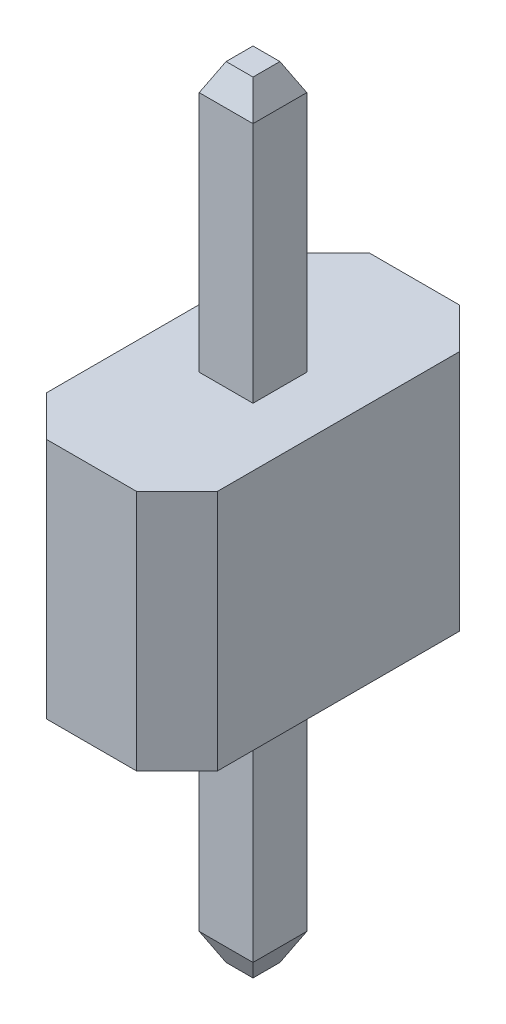
SolidWorks part; units mm, degrees
ref_plane "前视基准面" through (0, 0, 0) normal (0, 0, 1) x (1, 0, 0)
ref_plane "上视基准面" through (0, 0, 0) normal (0, 1, 0) x (1, 0, 0)
ref_plane "右视基准面" through (0, 0, 0) normal (1, 0, 0) x (0, 0, -1)
sketch "草图1" plane through (0, 0, 0) normal (0, 1, 0) x (1, 0, 0)
  line L1 (-0.635, 1.2) -> (0.635, 1.2)
  line L2 (-0.635, 1.2) -> (-0.635, -1.2)
  line L3 (-0.635, -1.2) -> (0.635, -1.2)
  line L4 (0.635, 1.2) -> (0.635, -1.2)
  line L5 (-0.635, 1.2) -> (0.635, -1.2) construction
  line L6 (-0.635, -1.2) -> (0.635, 1.2) construction
  point P0 (0, 0)
  dimension "D1" = 1.27
  dimension "D2" = 2.4
extrude "凸台-拉伸1" add sketch "草图1" along normal blind 1.8
sketch "草图2" plane through (0, 1.8, 0) normal (0, 1, 0) x (1, 0, 0)
  line L1 (-0.2, 0.2) -> (0.2, 0.2)
  line L2 (-0.2, 0.2) -> (-0.2, -0.2)
  line L3 (-0.2, -0.2) -> (0.2, -0.2)
  line L4 (0.2, 0.2) -> (0.2, -0.2)
  line L5 (-0.2, 0.2) -> (0.2, -0.2) construction
  line L6 (-0.2, -0.2) -> (0.2, 0.2) construction
  point P0 (0, 0)
  dimension "D1" = 0.4
extrude "凸台-拉伸2" add sketch "草图2" along normal blind 2 and the other way blind 3.8
sketch "草图3" plane through (0, 1.8, 0) normal (0, 1, 0) x (1, 0, 0)
  line L0 (-0.335, 1.2) -> (-0.635, 0.9)
  line L1 (0.635, 1.2) -> (-0.635, 1.2) construction
  line L2 (-0.635, 1.2) -> (-0.635, -1.2) construction
  line L3 (-0.635, 0.9) -> (-0.635, 1.2)
  line L4 (-0.635, 1.2) -> (-0.335, 1.2)
  line L5 (0, 1.2) -> (0, -1.2) construction
  line L6 (-0.635, -1.2) -> (0.635, -1.2) construction
  line L7 (-0.635, 0) -> (0.635, 0) construction
  line L8 (0.635, -1.2) -> (0.635, 1.2) construction
  line L9 (0.635, 1.2) -> (0.335, 1.2)
  line L10 (0.635, 0.9) -> (0.635, 1.2)
  line L11 (0.335, 1.2) -> (0.635, 0.9)
  line L12 (0.335, -1.2) -> (0.635, -0.9)
  line L13 (0.635, -0.9) -> (0.635, -1.2)
  line L14 (0.635, -1.2) -> (0.335, -1.2)
  line L15 (-0.635, -1.2) -> (-0.335, -1.2)
  line L16 (-0.635, -0.9) -> (-0.635, -1.2)
  line L17 (-0.335, -1.2) -> (-0.635, -0.9)
  dimension "D1" = 0.3
extrude "切除-拉伸1" cut sketch "草图3" against normal through all
chamfer "倒角1" distance 0.2 distance2 0.1 4 edges at (0, 3.8, 0.2) (-0.2, 3.8, 0) (0, 3.8, -0.2) (0.2, 3.8, 0)
chamfer "倒角2" distance 0.1 distance2 0.2 4 edges at (0, -2, -0.2) (-0.2, -2, 0) (0, -2, 0.2) (0.2, -2, 0)
